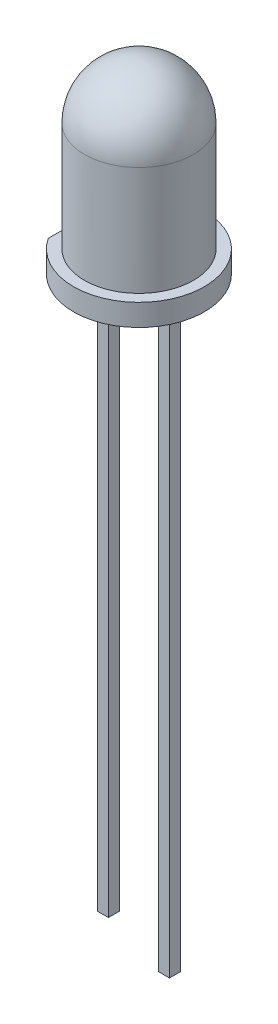
SolidWorks part; units mm, degrees
ref_plane "Front Plane" through (0, 0, 0) normal (0, 0, 1) x (1, 0, 0)
ref_plane "Top Plane" through (0, 0, 0) normal (0, 1, 0) x (1, 0, 0)
ref_plane "Right Plane" through (0, 0, 0) normal (1, 0, 0) x (0, 0, -1)
sketch "Sketch1" plane through (0, 0, 0) normal (0, 1, 0) x (1, 0, 0)
  line L0 (-2.5, 1.6583) -> (-2.5, -1.6583)
  arc A0 (-2.5, -1.6583) -> (-2.5, 1.6583) centre (0, 0) ccw
  dimension "D1" = 6
  dimension "D2" = 2.5
extrude "Boss-Extrude1" add sketch "Sketch1" along normal blind 1
sketch "Sketch2" plane through (0, 1, 0) normal (0, 1, 0) x (1, 0, 0)
  circle A0 centre (0, 0) radius 2.5
  dimension "D1" = 5
extrude "Boss-Extrude2" add sketch "Sketch2" along normal blind 7.5
fillet "Fillet1" radius 2.5 1 edges at (0, 8.5, 2.5)
sketch "Sketch3" plane through (0, 0, 0) normal (0, 1, 0) x (1, 0, 0)
  line L0 (0, -3.3) -> (0, 3.3) construction
  line L1 (-1.65, 0.25) -> (-1.15, 0.25)
  line L2 (-1.65, 0.25) -> (-1.65, -0.25)
  line L3 (-1.65, -0.25) -> (-1.15, -0.25)
  line L4 (-1.15, 0.25) -> (-1.15, -0.25)
  line L5 (-1.65, 0.25) -> (-1.15, -0.25) construction
  line L6 (-1.65, -0.25) -> (-1.15, 0.25) construction
  line L7 (1.65, -0.25) -> (1.15, -0.25)
  line L8 (1.15, 0.25) -> (1.15, -0.25)
  line L9 (1.65, 0.25) -> (1.15, 0.25)
  line L10 (1.65, 0.25) -> (1.65, -0.25)
  point P0 (-1.4, 0)
  dimension "D1" = 1.4
  dimension "D2" = 0.5
extrude "Boss-Extrude3" add sketch "Sketch3" against normal blind 26
sketch "Sketch4" plane through (0, -26, 0) normal (0, -1, 0) x (1, 0, 0)
  line L1 (1.15, -0.25) -> (1.65, -0.25)
  line L2 (1.15, -0.25) -> (1.15, 0.25)
  line L3 (1.15, 0.25) -> (1.65, 0.25)
  line L4 (1.65, -0.25) -> (1.65, 0.25)
extrude "Boss-Extrude4" add sketch "Sketch4" along normal blind 1
